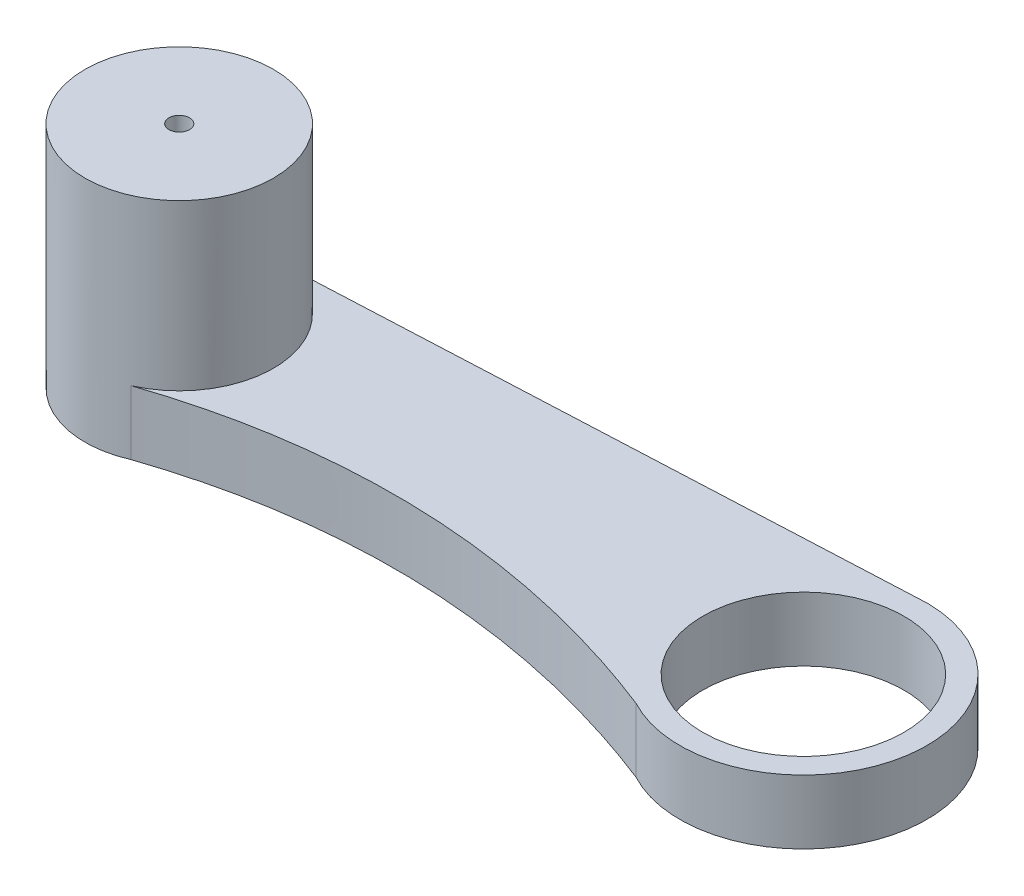
SolidWorks part; units mm, degrees
ref_plane "Płaszczyzna przednia" through (0, 0, 0) normal (0, 0, 1) x (1, 0, 0)
ref_plane "Płaszczyzna górna" through (0, 0, 0) normal (0, 1, 0) x (1, 0, 0)
ref_plane "Płaszczyzna prawa" through (0, 0, 0) normal (1, 0, 0) x (0, 0, -1)
sketch "Szkic1" plane through (0, 0, 0) normal (0, 1, 0) x (1, 0, 0)
  circle A0 centre (0, 0) radius 10.3
  circle A1 centre (0, 0) radius 1.125
  dimension "D1" = 20.6
  dimension "D2" = 2.25
extrude "Dodanie-wyciągnięcie1" add sketch "Szkic1" along normal blind 25 contours A0
hole_wizard "Otwory ustalające Ø2.5mm2" positions "Szkic4" profile "Szkic6" hole size "Ø2.5" standard "Ansi Metric" end condition through all
sketch "Szkic4" plane through (0, 0, 0) normal (0, -1, 0) x (1, 0, 0)
  point P0 (0, 0)
sketch "Szkic6" plane through (0, 0, 0) normal (1, 0, 0) x (0, 0, -1)
  line L0 (0, 0) -> (0, 25)
  line L1 (0, 25) -> (1.125, 25)
  line L2 (1.125, 25) -> (1.125, 0)
  line L5 (1.125, 0) -> (0, 0)
  line L11 (0, -6.35) -> (0, 107.95) construction
  dimension "Średnica otworu na wylot" = 2.25
  dimension "Głębokość otworu na wylot" = 25
sketch "Szkic7" plane through (0, 25, 0) normal (0, 1, 0) x (1, 0, 0)
  line L0 (0, 0) -> (10.1903, 0) construction
  line L1 (10.1903, 0) -> (68.2073, 0) construction
  line L2 (4.1699, -9.4182) -> (22.4618, -3.246) construction
  line L3 (22.4618, -3.246) -> (41.9342, -4.0772) construction
  line L4 (41.9342, -4.0772) -> (61.82, -11.8934) construction
  line L5 (66.9434, 13.4407) -> (0, 10.3)
  arc A0 (61.82, -11.8934) -> (66.9434, 13.4407) centre (68.2073, 0) ccw
  circle A1 centre (0, 0) radius 10.3 construction
  arc A2 (0, 10.3) -> (4.1699, -9.4182) centre (0, 0) cw
  spline S0 degree 3 poles (4.1699, -9.4182) (22.4618, -3.246) (41.9342, -4.0772) (61.82, -11.8934) knots 0 0 0 0 1 1 1 1
  dimension "D1" = 27
extrude "Dodanie-wyciągnięcie3" add sketch "Szkic7" against normal blind 7
hole_wizard "Otwory ustalające Ø2.5mm3" positions "Szkic10" profile "Szkic11" hole size "Ø2.5" standard "Ansi Metric" end condition through all
sketch "Szkic10" plane through (0, 25, 0) normal (0, 1, 0) x (1, 0, 0)
  point P0 (68.2073, 0)
sketch "Szkic11" plane through (68.2073, 25, 0) normal (1, 0, 0) x (0, 0, 1)
  line L0 (0, 0) -> (0, 25)
  line L1 (0, 25) -> (11, 25)
  line L2 (11, 25) -> (11, 0)
  line L5 (11, 0) -> (0, 0)
  line L11 (0, -6.35) -> (0, 107.95) construction
  dimension "Średnica otworu na wylot" = 22
  dimension "Głębokość otworu na wylot" = 25
mirror "Lustro1" about plane through (0, 0, 0) normal (0, 1, 0) of bodies 106
delete or keep bodies "Obiekt-Usuń/zachowaj 1" type delete bodies bodies 106
